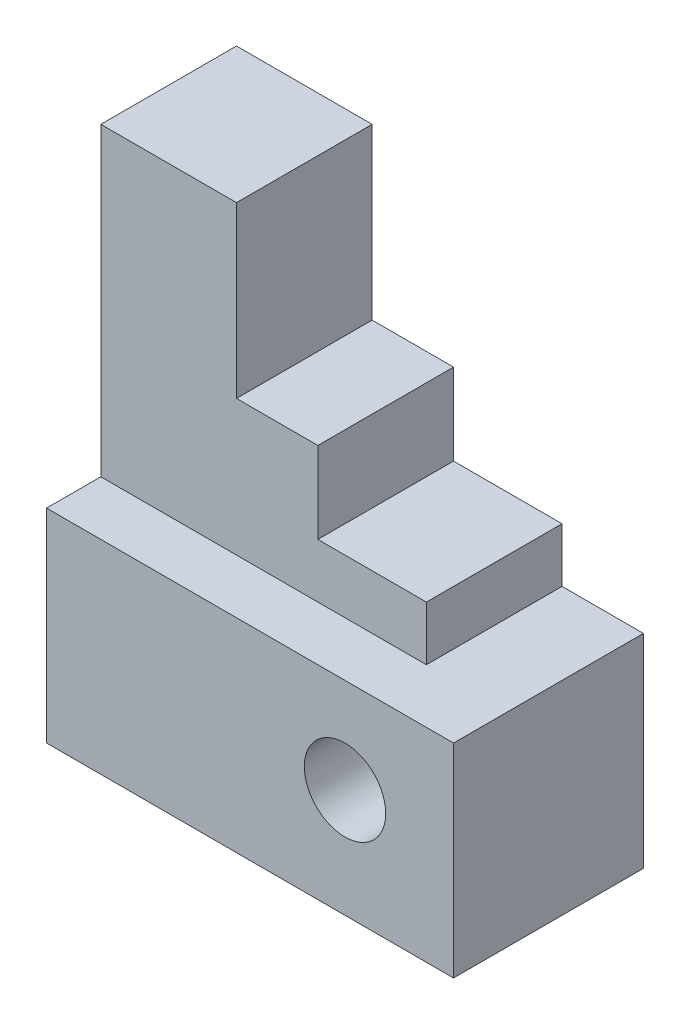
SolidWorks part; units mm, degrees
ref_plane "Front Plane" through (0, 0, 0) normal (0, 0, 1) x (1, 0, 0)
ref_plane "Top Plane" through (0, 0, 0) normal (0, 1, 0) x (1, 0, 0)
ref_plane "Right Plane" through (0, 0, 0) normal (1, 0, 0) x (0, 0, -1)
sketch "Croquis1" plane through (0, 0, 0) normal (0, 0, 1) x (1, 0, 0)
  line L0 (-33.4476, 2.0829) -> (26.5524, 2.0829)
  line L1 (26.5524, 2.0829) -> (26.5524, 32.0829)
  line L2 (-33.4476, 2.0829) -> (-33.4476, 77.0829)
  line L3 (-33.4476, 77.0829) -> (-13.4476, 77.0829)
  line L4 (26.5524, 32.0829) -> (14.5524, 32.0829)
  line L5 (-13.4476, 77.0829) -> (-13.4476, 52.0829)
  line L6 (-13.4476, 52.0829) -> (-1.4476, 52.0829)
  line L7 (-1.4476, 52.0829) -> (-1.4476, 40.0829)
  line L8 (-1.4476, 40.0829) -> (14.5524, 40.0829)
  line L9 (14.5524, 40.0829) -> (14.5524, 32.0829)
  circle A0 centre (10.5524, 18.0829) radius 6
  point P12 (0, 0)
  point P13 (0, 0)
  dimension "D9" = 12
  dimension "D10" = 16
  dimension "D1" = 60
  dimension "D2" = 30
  dimension "D3" = 75
  dimension "D4" = 20
  dimension "D5" = 12
  dimension "D6" = 12
  dimension "D7" = 12
  dimension "D8" = 20
  dimension "D11" = 16
extrude "Saliente-Extruir2" add sketch "Croquis1" along normal blind 28 contours L9 L4 L1 L0 L2 L3 L5 L6 L7 L8 | A0
sketch "Croquis2" plane through (0, 0, 28) normal (0, 0, 1) x (1, 0, 0)
  line L0 (26.5524, 32.0829) -> (-33.4476, 32.0829)
  line L1 (-33.4476, 2.0829) -> (-33.4476, 77.0829) construction
  line L2 (-33.4476, 32.0829) -> (-33.4476, 77.0829)
  line L3 (-33.4476, 77.0829) -> (26.5524, 77.0829)
  line L4 (26.5524, 77.0829) -> (26.5524, 32.0829)
extrude "Cortar-Extruir2" cut sketch "Croquis2" against normal blind 8 contours L4 L0 L2 L3
equation "\"8..00mm\"=28"
